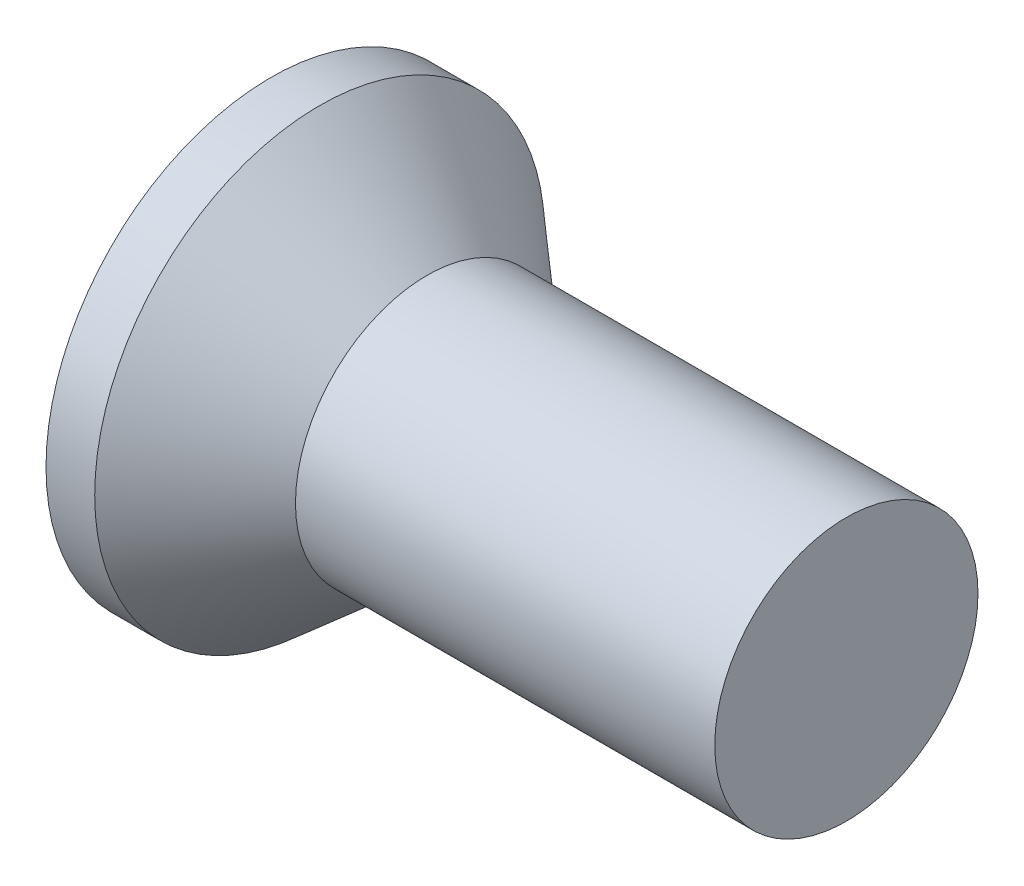
SolidWorks part; units mm, degrees
material "Alloy Steel"
ref_plane "Plane1" through (0, 0, 0) normal (0, 0, 1) x (1, 0, 0)
ref_plane "Plane2" through (0, 0, 0) normal (0, 1, 0) x (1, 0, 0)
ref_plane "Plane3" through (0, 0, 0) normal (1, 0, 0) x (0, 0, -1)
revolve "Base-Revolve" add sketch "BodySke" angle 360 about L5
sketch "BodySke" plane through (0, 0, 0) normal (0, 0, 1) x (1, 0, 0)
  line L0 (0, 0) -> (0, 1.8669)
  line L1 (0, 1.8669) -> (0.4042, 1.8669)
  line L2 (1.2954, 1.0922) -> (4.7752, 1.0922)
  line L3 (4.7752, 1.0922) -> (4.7752, 0)
  line L4 (4.7752, 0) -> (0, 0)
  line L5 (-6.35, 0) -> (82.55, 0) construction
  line L6 (1.2954, -1.0922) -> (4.7752, -1.0922) construction
  line L7 (0.4042, -1.8669) -> (1.2954, -1.0922) construction
  line L8 (0.4042, 1.8669) -> (1.2954, 1.0922)
  line L9 (0, -1.8669) -> (0.4042, -1.8669) construction
  line L10 (1.7501, 2.6797) -> (1.7501, -6.8453) construction
  line L11 (0, 6.35) -> (0, -3.175) construction
  dimension "Diameter" = 2.1844
  dimension "Length" = 4.7752
  dimension "Head_ht" = 1.2954
  dimension "Head_dia" = 3.7338
  dimension "Head_ang" = 82
  dimension "D6" = 0.4042
  dimension "Advance" = 0.4547
  dimension "Thread_nom" = 4.7752
cosmetic thread "ThreadCosmetic" parameters "Thread_length"=3.0251, "Thread_minor"=1.6459
extrude "Slot" cut sketch "Sketch2" against normal blind 0.5842
sketch "Sketch2" plane through (0, 0, 0) normal (-1, 0, 0) x (0, 0, 1)
  line L0 (-1.8669, -0.3937) -> (1.8669, -0.3937)
  line L1 (-1.8669, -0.3937) -> (-1.8669, 0.3937)
  line L2 (1.8669, 0.3937) -> (-1.8669, 0.3937)
  line L3 (1.8669, 0.3937) -> (1.8669, -0.3937)
  dimension "D1" = 0.3937
  dimension "Slot_width" = 0.7874
  dimension "D2" = 3.7338
  dimension "D3" = 1.8669
sketch "Sketch3" plane through (0, 0, 0) normal (-1, 0, 0) x (0, 0, 1)
  line L0 (-0.3429, 1.524) -> (0.3429, 1.524)
  line L1 (0.3429, 1.524) -> (0.3429, -1.524)
  line L2 (0.3429, -1.524) -> (-0.3429, -1.524)
  line L3 (-0.3429, -1.524) -> (-0.3429, 1.524)
  dimension "D1" = 1.524
  dimension "Cross_dia" = 3.048
  dimension "D2" = 0.3429
  dimension "Cross_width" = 0.6858
ref_plane "Plane4" through (1.6764, 0, 0) normal (-1, 0, 0) x (0, 0, 1)
sketch "Sketch4" plane through (1.6764, 0, 0) normal (-1, 0, 0) x (0, 0, 1)
  line L0 (-0.1714, 0.1714) -> (0.1715, 0.1714)
  line L3 (0.1715, 0.1714) -> (0.1715, -0.1715)
  line L4 (0.1715, -0.1715) -> (-0.1714, -0.1715)
  line L5 (-0.1714, -0.1715) -> (-0.1714, 0.1714)
  dimension "D1" = 0.3429
  dimension "D2" = 0.3429
  dimension "D3" = 0.1714
  dimension "D4" = 0.1714
loft "Cross" cut profiles "Sketch3", "Sketch4"
pattern_circular "CirPattern1" count 2 every 90 about axis through (0, 0, 0) along (1, 0, 0) of "Cross"
equation "\"D1@Sketch3\" = \"Cross_dia@Sketch3\" / 2"
equation "\"D2@Sketch3\" = \"Cross_width@Sketch3\" / 2"
equation "\"D1@Sketch4\" = \"Cross_width@Sketch3\" *.5"
equation "\"D2@Sketch4\" = \"D1@Sketch4\""
equation "\"D4@Sketch4\" = \"D2@Sketch4\" / 2"
equation "\"D3@Sketch4\" = \"D1@Sketch4\" / 2"
equation "\"D1@Sketch2\" = \"Slot_width@Sketch2\" / 2"
equation "\"D2@Sketch2\" = \"Head_dia@BodySke\""
equation "\"D3@Sketch2\" = \"D2@Sketch2\" / 2"
equation "\"Thread_length@ThreadCosmetic\" = ((sgn( (\"Length@BodySke\" - \"Advance@BodySke\" - \"Head_ht@BodySke\" ) - \"Thread_nom@BodySke\" )-1)*( (\"Length@BodySke\" - \"Advance@BodySke\" - \"Head_ht@BodySke\" ) - \"Thread_nom@BodySke\" ))/-2+ \"Thread_nom@BodySke\""
